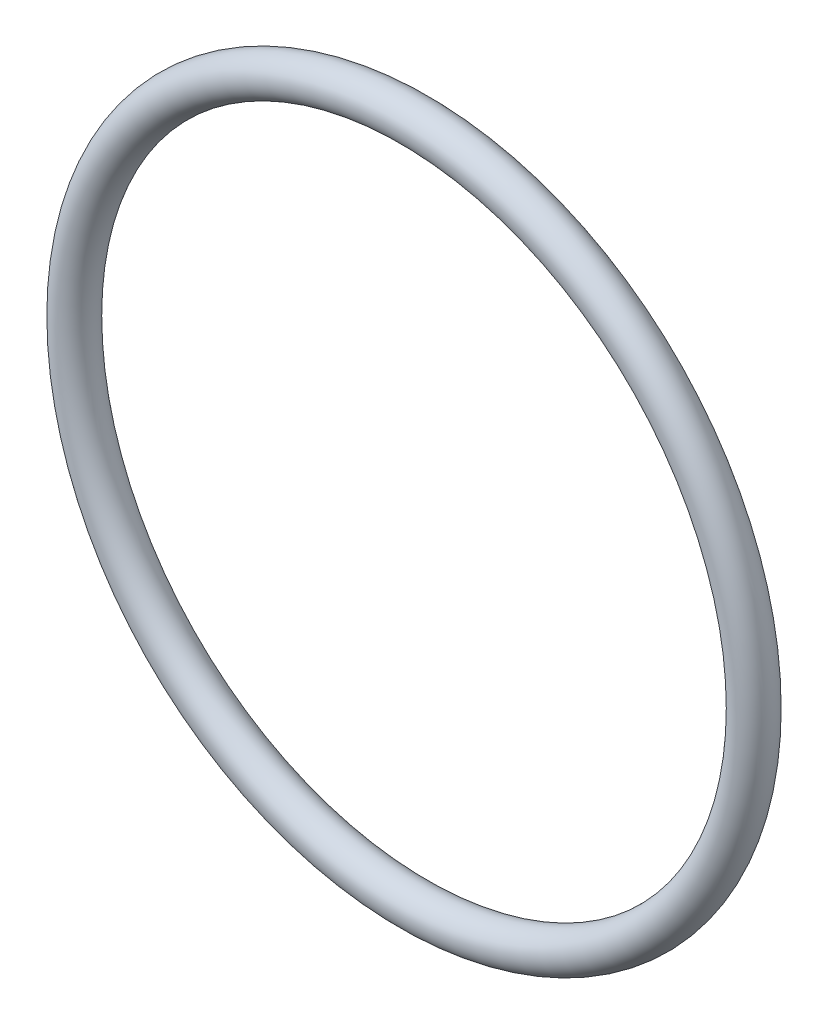
SolidWorks part; units mm, degrees
material "NBR"
ref_plane "Horní rovina" through (0, 0, 0) normal (0, 0, 1) x (1, 0, 0)
ref_plane "Přední rovina" through (0, 0, 0) normal (0, 1, 0) x (1, 0, 0)
ref_plane "Pravá rovina" through (0, 0, 0) normal (1, 0, 0) x (0, 0, -1)
sketch "Skica1" plane through (0, 0, 0) normal (0, 1, 0) x (1, 0, 0)
  line L0 (-17.5, 35.2404) -> (-17.5, 0) construction
  line L1 (-1, 2.1037) -> (-1, -2.0568) construction
  line L2 (-17.5, 0) -> (0, 0) construction
  circle A0 centre (0, 0) radius 1
  dimension "D1" = 2
  dimension "D2" = 17.5
revolve "Rotovat1" add sketch "Skica1" angle 360 about L0
sketch "Skica2" plane through (0, 0, 0) normal (0, 0, 1) x (1, 0, 0)
  line L0 (-17.5, 0) -> (0, 0) construction
  line L1 (-17.5, 0) -> (0, 0) construction
  circle A1 centre (-17.5, 0) radius 17.5
